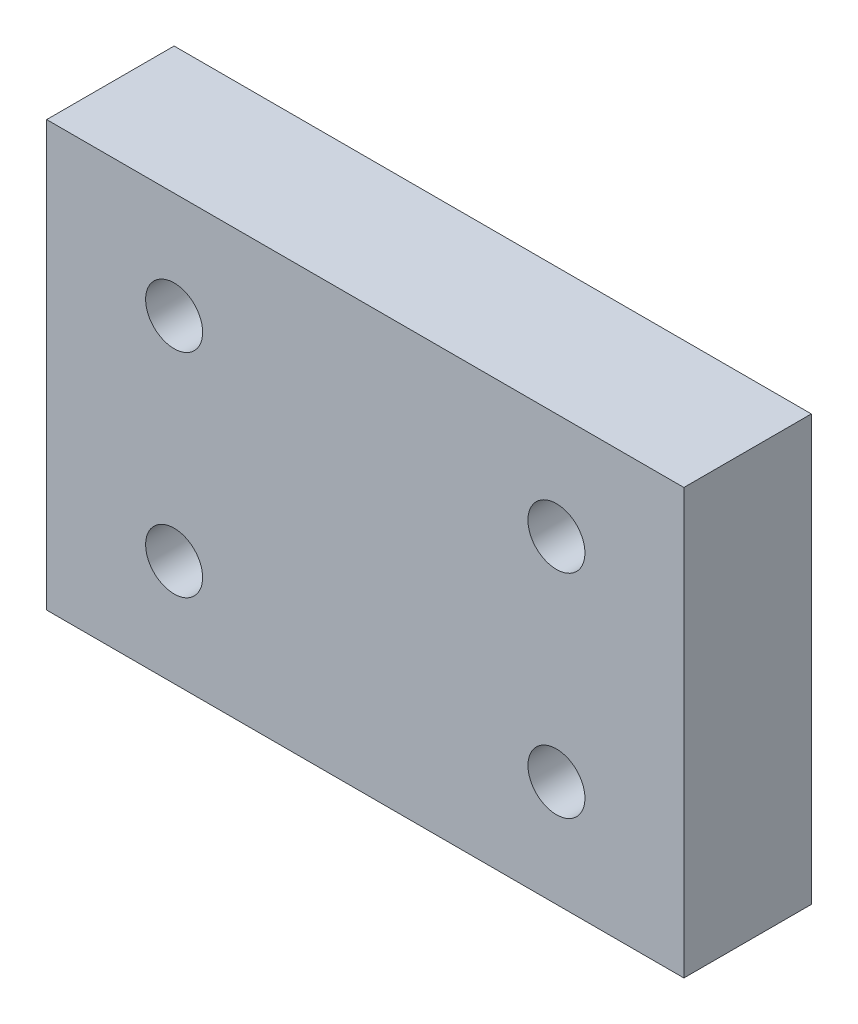
SolidWorks part; units mm, degrees
ref_plane "Plan de face" through (0, 0, 0) normal (0, 0, 1) x (1, 0, 0)
ref_plane "Plan de dessus" through (0, 0, 0) normal (0, 1, 0) x (1, 0, 0)
ref_plane "Plan de droite" through (0, 0, 0) normal (1, 0, 0) x (0, 0, -1)
sketch "Esquisse1" plane through (0, 0, 0) normal (0, 0, 1) x (1, 0, 0)
  line L0 (15, 20) -> (15, 0) construction
  line L1 (0, 0) -> (30, 0)
  line L2 (0, 0) -> (0, 20)
  line L3 (0, 20) -> (30, 20)
  line L4 (30, 0) -> (30, 20)
  line L5 (0, 10) -> (30, 10) construction
  circle A0 centre (6, 15) radius 1.3418
  circle A1 centre (24, 15) radius 1.3418
  circle A2 centre (24, 5) radius 1.3418
  circle A3 centre (6, 5) radius 1.3418
  dimension "D1" = 30
  dimension "D2" = 20
  dimension "D3" = 5
  dimension "D4" = 6
extrude "Boss.-Extru.1" add sketch "Esquisse1" along normal blind 6
